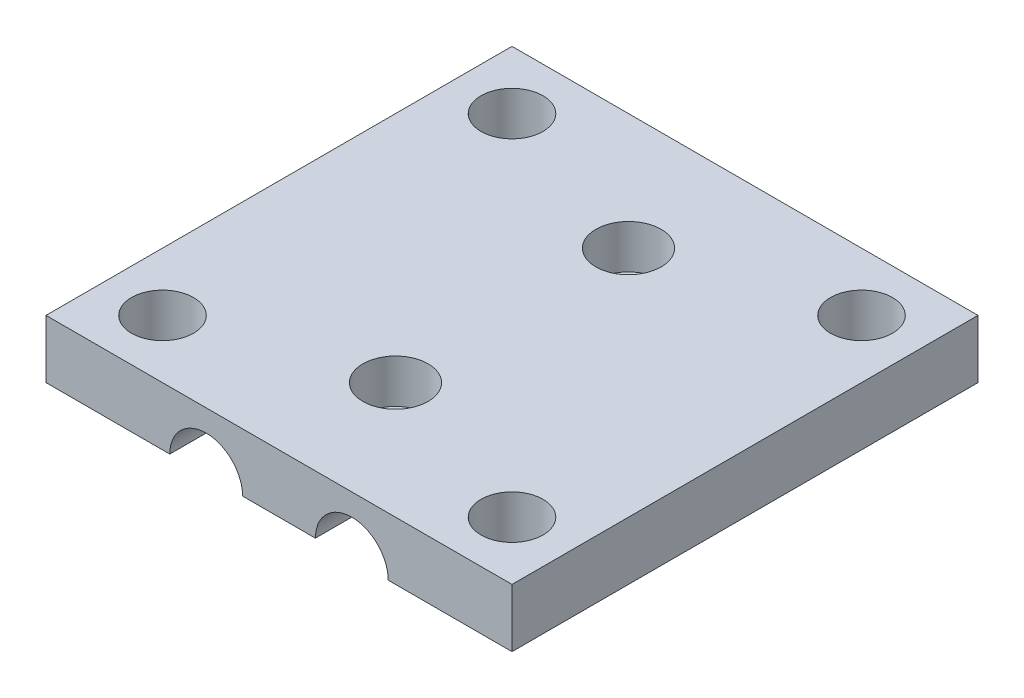
SolidWorks part; units mm, degrees
ref_plane "Front Plane" through (0, 0, 0) normal (0, 0, 1) x (1, 0, 0)
ref_plane "Top Plane" through (0, 0, 0) normal (0, 1, 0) x (1, 0, 0)
ref_plane "Right Plane" through (0, 0, 0) normal (1, 0, 0) x (0, 0, -1)
sketch "Sketch1" plane through (0, 0, 0) normal (0, 1, 0) x (1, 0, 0)
  line L1 (-25.4, 25.4) -> (25.4, 25.4)
  line L2 (-25.4, 25.4) -> (-25.4, -25.4)
  line L3 (-25.4, -25.4) -> (25.4, -25.4)
  line L4 (25.4, 25.4) -> (25.4, -25.4)
  dimension "D1" = 50.8
  dimension "D2" = 50.8
  dimension "D3" = 25.4
  dimension "D4" = 25.4
extrude "Boss-Extrude1" add sketch "Sketch1" along normal blind 6.35
sketch "Sketch2" plane through (0, 0, 25.4) normal (0, 0, 1) x (1, 0, 0)
  line L0 (-25.4, 0) -> (25.4, 0) construction
  circle A0 centre (-7.9375, 0) radius 3.9688
  circle A1 centre (7.9375, 0) radius 3.9688
  dimension "D1" = 7.9375
  dimension "D2" = 7.9375
  dimension "D3" = 7.9375
  dimension "D4" = 7.9375
extrude "Cut-Extrude1" cut sketch "Sketch2" against normal through all
hole_wizard "1/4 Clearance Hole1" positions "Sketch5" profile "Sketch4" hole size "1/4" standard "ANSI Inch" end condition through all
sketch "Sketch5" plane through (0, 6.35, 0) normal (0, 1, 0) x (1, 0, 0)
  point P0 (-19.05, -19.05)
  point P2 (-19.05, 19.05)
  point P4 (19.05, 19.05)
  point P6 (19.05, -19.05)
sketch "Sketch4" plane through (-19.05, 6.35, 19.05) normal (1, 0, 0) x (0, 0, 1)
  line L0 (0, 0) -> (0, 6.35)
  line L1 (0, 6.35) -> (3.3782, 6.35)
  line L2 (3.3782, 6.35) -> (3.3782, 0)
  line L5 (3.3782, 0) -> (0, 0)
  line L11 (0, -6.35) -> (0, 107.95) construction
  dimension "Thru Hole Dia." = 6.7564
  dimension "Thru Hole Depth" = 6.35
hole_wizard "#8 Clearance Hole1" positions "Sketch9" profile "Sketch8" hole size "#8" standard "ANSI Inch" end condition through all
sketch "Sketch9" plane through (0, 6.35, 0) normal (0, 1, 0) x (1, 0, 0)
  point P0 (0, 12.7)
  point P2 (0, -12.7)
sketch "Sketch8" plane through (0, 6.35, -12.7) normal (1, 0, 0) x (0, 0, 1)
  line L0 (0, 0) -> (0, 6.35)
  line L1 (0, 6.35) -> (2.2479, 6.35)
  line L2 (2.2479, 6.35) -> (2.2479, 0)
  line L5 (2.2479, 0) -> (0, 0)
  line L11 (0, -6.35) -> (0, 107.95) construction
  dimension "Thru Hole Dia." = 4.4958
  dimension "Thru Hole Depth" = 6.35
sketch "Sketch10" plane through (0, 6.35, 0) normal (0, 1, 0) x (1, 0, 0)
  circle A0 centre (0, 12.7) radius 3.556
  circle A1 centre (0, -12.7) radius 3.556
  dimension "D1" = 7.112
  dimension "D2" = 7.112
extrude "Cut-Extrude2" cut sketch "Sketch10" against normal blind 4.7625
